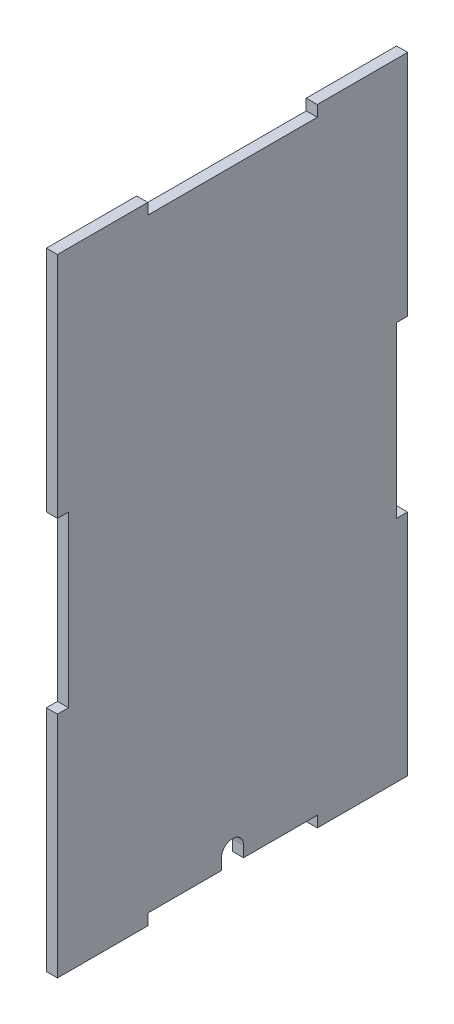
SolidWorks part; units mm, degrees
ref_plane "Alzado" through (0, 0, 0) normal (0, 0, 1) x (1, 0, 0)
ref_plane "Planta" through (0, 0, 0) normal (0, 1, 0) x (1, 0, 0)
ref_plane "Vista lateral" through (0, 0, 0) normal (1, 0, 0) x (0, 0, -1)
sketch "Croquis1" plane through (0, 0, 0) normal (1, 0, 0) x (0, 0, -1)
  line L0 (24.5, 167) -> (70.5, 167)
  line L1 (0, 170) -> (24.5, 170)
  line L2 (0, 170) -> (0, 108)
  line L3 (0, 0) -> (24.5, 0)
  line L4 (95, 170) -> (95, 108)
  line L5 (70.5, 167) -> (70.5, 170)
  line L6 (24.5, 167) -> (24.5, 170)
  line L7 (24.5, 3) -> (44.5, 3)
  line L8 (92, 62) -> (92, 108)
  line L9 (3, 62) -> (3, 108)
  line L10 (3, 62) -> (0, 62)
  line L11 (3, 108) -> (0, 108)
  line L12 (92, 108) -> (95, 108)
  line L13 (92, 62) -> (95, 62)
  line L14 (70.5, 3) -> (70.5, 0)
  line L15 (24.5, 3) -> (24.5, 0)
  line L16 (0, 62) -> (0, 0)
  line L17 (70.5, 170) -> (95, 170)
  line L18 (95, 62) -> (95, 0)
  line L19 (70.5, 0) -> (95, 0)
  line L20 (50.5, 3) -> (50.5, 6)
  line L21 (44.5, 3) -> (44.5, 6)
  line L22 (50.5, 3) -> (70.5, 3)
  line L23 (44.5, 3) -> (50.5, 3) construction
  arc A2 (44.5, 6) -> (50.5, 6) centre (47.5, 6) cw
  point P9 (47.5, 3)
  point P10 (47.5, 167)
  point P13 (0, 0)
  dimension "D3" = 6
  dimension "D1" = 95
  dimension "D2" = 170
  dimension "D4" = 3
  dimension "D9" = 46
  dimension "D10" = 3
  dimension "D11" = 46
  dimension "D12" = 46
  dimension "D13" = 3
  dimension "D14" = 3
  dimension "D15" = 46
  dimension "D16" = 3
  dimension "D17" = 62
  dimension "D18" = 24.5
  dimension "D19" = 62
  dimension "D20" = 24.5
extrude "Saliente-Extruir1" add sketch "Croquis1" along normal blind 3
